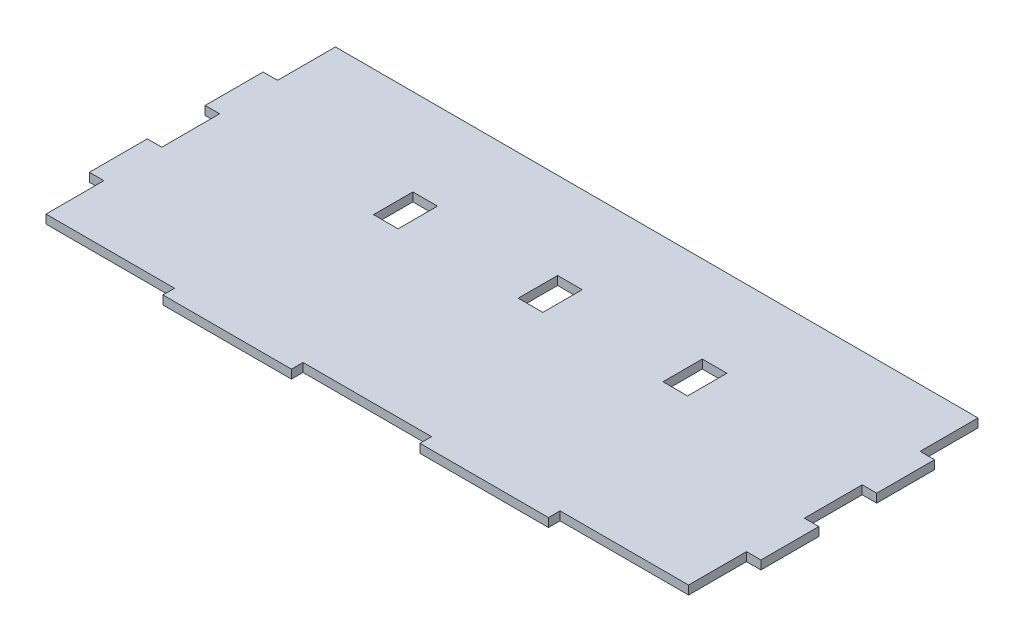
SolidWorks part; units mm, degrees
ref_plane "Front Plane" through (0, 0, 0) normal (0, 0, 1) x (1, 0, 0)
ref_plane "Top Plane" through (0, 0, 0) normal (0, 1, 0) x (1, 0, 0)
ref_plane "Right Plane" through (0, 0, 0) normal (1, 0, 0) x (0, 0, -1)
sketch "Sketch1" plane through (0, 0, 0) normal (0, 1, 0) x (1, 0, 0)
  line L0 (-111, 30) -> (-116, 30)
  line L1 (-111, -50) -> (-66.6, -50)
  line L2 (-111, -50) -> (-111, -30)
  line L3 (-111, 50) -> (111, 50)
  line L4 (111, -50) -> (111, -30)
  line L5 (-111, -50) -> (111, 50) construction
  line L6 (-111, 50) -> (111, -50) construction
  line L7 (-116, 30) -> (-116, 10)
  line L8 (-116, 10) -> (-111, 10)
  line L9 (0, 50) -> (0, -50) construction
  line L10 (-111, -10) -> (-116, -10)
  line L11 (-116, -10) -> (-116, -30)
  line L12 (-116, -30) -> (-111, -30)
  line L13 (-111, 30) -> (-111, 50)
  line L14 (-111, -10) -> (-111, 10)
  line L15 (116, -30) -> (111, -30)
  line L16 (116, -10) -> (116, -30)
  line L17 (111, -10) -> (116, -10)
  line L18 (116, 10) -> (111, 10)
  line L19 (116, 30) -> (116, 10)
  line L20 (111, 30) -> (116, 30)
  line L21 (111, 30) -> (111, 50)
  line L22 (111, -10) -> (111, 10)
  line L23 (-22.2, -50) -> (22.2, -50)
  line L24 (-66.6, -54) -> (-22.2, -54)
  line L25 (-66.6, -54) -> (-66.6, -50)
  line L27 (-22.2, -54) -> (-22.2, -50)
  line L28 (22.2, -54) -> (22.2, -50)
  line L29 (66.6, -54) -> (66.6, -50)
  line L30 (22.2, -54) -> (66.6, -54)
  line L31 (66.6, -50) -> (111, -50)
  line L32 (-4.25, 6.4) -> (-4.25, 20)
  line L33 (-4.25, 6.4) -> (4.25, 6.4)
  line L34 (-54.25, 6.4) -> (-45.75, 6.4)
  line L35 (-54.25, 6.4) -> (-54.25, 20)
  line L36 (-54.25, 20) -> (-45.75, 20)
  line L37 (-45.75, 6.4) -> (-45.75, 20)
  line L38 (-54.25, 6.4) -> (-45.75, 20) construction
  line L39 (-54.25, 20) -> (-45.75, 6.4) construction
  line L44 (4.25, 6.4) -> (4.25, 20)
  line L45 (-4.25, 20) -> (4.25, 20)
  line L50 (45.75, 6.4) -> (45.75, 20)
  line L51 (45.75, 6.4) -> (54.25, 6.4)
  line L52 (54.25, 6.4) -> (54.25, 20)
  line L53 (45.75, 20) -> (54.25, 20)
  point P0 (0, 0)
  point P34 (-50, 13.2)
  dimension "D1" = 222
  dimension "D2" = 100
  dimension "D3" = 20
  dimension "D4" = 20
  dimension "D5" = 5
  dimension "D7" = 44.4
  dimension "D8" = 2
  dimension "D9" = 44.4
  dimension "D10" = 4
  dimension "D11" = 8.5
  dimension "D12" = 13.6
  dimension "D13" = 50
  dimension "D15" = 30
  dimension "D6" = 2
  dimension "D14" = 3
extrude "Boss-Extrude1" add sketch "Sketch1" along normal blind 3
